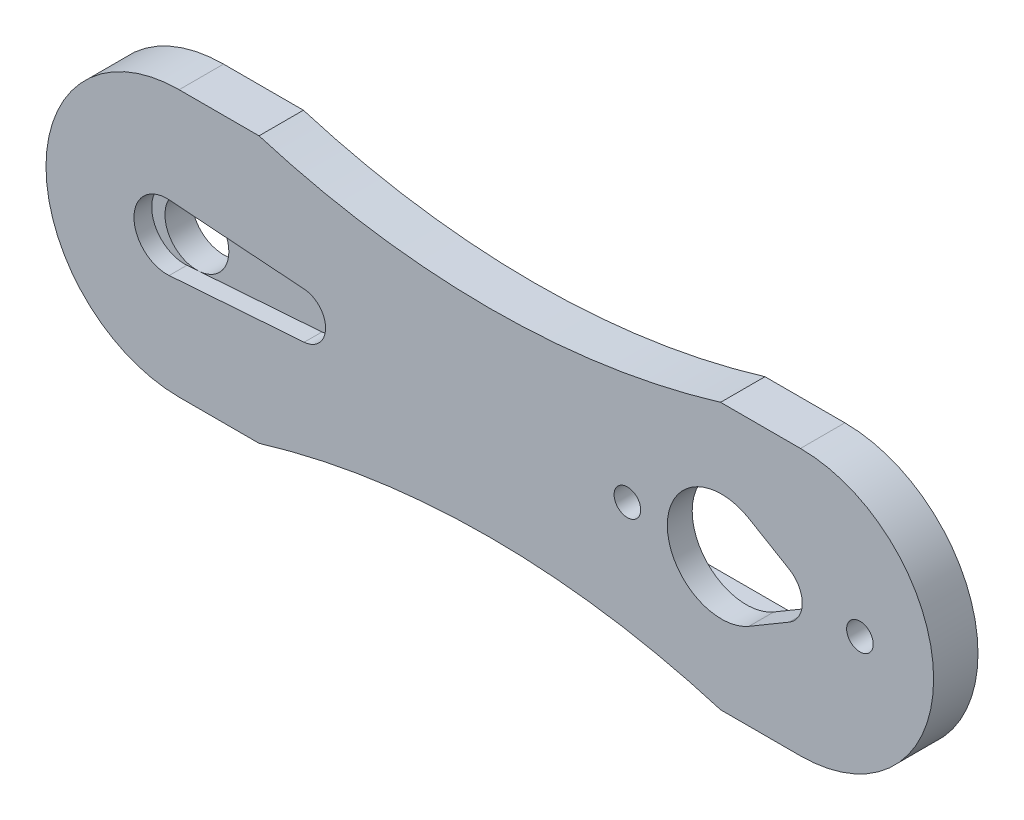
SolidWorks part; units mm, degrees
ref_plane "Front Plane" through (0, 0, 0) normal (0, 0, 1) x (1, 0, 0)
ref_plane "Top Plane" through (0, 0, 0) normal (0, 1, 0) x (1, 0, 0)
ref_plane "Right Plane" through (0, 0, 0) normal (1, 0, 0) x (0, 0, -1)
ref_plane "Plane1" through (0, 0, 0) normal (0, 0, -1) x (-1, 0, 0)
sketch "Sketch1" plane through (0, 0, 0) normal (0, 0, -1) x (-1, 0, 0)
  line L0 (-70, 0) -> (-61, 0)
  line L1 (0, 0) -> (-9, 0)
  line L2 (0, -15) -> (-10.6343, -15) construction
  line L3 (0, -30) -> (-9, -30)
  line L4 (-70, -30) -> (-61, -30)
  arc A1 (-61, 0) -> (-9, 0) centre (-35, 86.1626) ccw
  arc A2 (-61, -30) -> (-9, -30) centre (-35, -116.1626) cw
  circle A9 centre (0, -15) radius 3.6
  arc A11 (-70, 0) -> (-70, -30) centre (-70, -15) ccw
  arc A15 (0, -30) -> (0, 0) centre (0, -15) ccw
  dimension "D1" = 7.2
  dimension "D2" = 9
  dimension "D3" = 90
  dimension "D10" = 15
  dimension "D11" = 100
extrude "Boss-Extrude1" add sketch "Sketch1" against normal blind 5
sketch "Croquis1" plane through (0, 0, 5) normal (0, 0, 1) x (1, 0, 0)
  line L0 (-1.1238, -11.3096) -> (14.0871, -12.4067)
  line L1 (14.0871, -17.5933) -> (-1.1238, -18.6904)
  circle A0 centre (0, -15) radius 3.6 construction
  arc A1 (14.0871, -12.4067) -> (14.0871, -17.5933) centre (13.9, -15) cw
  circle A2 centre (0, -15) radius 3.6
  arc A4 (-1.1238, -11.3096) -> (-1.1238, -18.6904) centre (-1.39, -15) ccw
  point P8 (0, 0)
  point P9 (-1.1238, -11.3096)
  circle M4 centre (0, -15) radius 3.6
  dimension "D1" = 2.6
  dimension "D2" = 16.5
  dimension "D3" = 3.7
extrude "Cortar-Extruir1" cut sketch "Croquis1" against normal blind 2 contours A1 L0 L1 M4 | L0 A4 L1 M4
sketch "Croquis3" plane through (0, 0, 0) normal (0, 0, -1) x (-1, 0, 0)
  line L1 (-80, -8.5) -> (-47, -8.5)
  line L2 (-80, -8.5) -> (-80, -21.5)
  line L3 (-80, -21.5) -> (-47, -21.5)
  line L4 (-47, -8.5) -> (-47, -21.5)
  arc A0 (0, -30) -> (0, 0) centre (0, -15) ccw construction
  arc A5 (-70, 0) -> (-70, -30) centre (-70, -15) ccw construction
  point P7 (15, -15)
  point P8 (-47, -15)
  dimension "D1" = 33
  dimension "D2" = 13
  dimension "D3" = 5
extrude "Cortar-Extruir2" cut sketch "Croquis3" against normal blind 2.2
sketch "Croquis4" plane through (0, 0, 2.2) normal (0, 0, -1) x (-1, 0, 0)
  line L0 (-64.2, -9.7464) -> (-68.7246, -12.4163)
  line L1 (-64.2, -20.2536) -> (-68.7246, -17.5837)
  line L2 (-47, -21.5) -> (-47, -8.5) construction
  line L5 (-80, -8.5) -> (-80, -21.5) construction
  arc A1 (-64.2, -20.2536) -> (-64.2, -9.7464) centre (-61.1, -15) ccw
  arc A3 (-68.7246, -12.4163) -> (-68.7246, -17.5837) centre (-67.2, -15) ccw
  point P12 (-47, -15)
  dimension "D1" = 3
  dimension "D2" = 12.2
  dimension "D3" = 25
  dimension "D4" = 15.2
extrude "Cortar-Extruir3" cut sketch "Croquis4" against normal blind 3
sketch "Croquis6" plane through (0, 0, 2.2) normal (0, 0, -1) x (-1, 0, 0)
  circle A0 centre (-50.5, -15) radius 1.5
  arc A2 (-64.2, -20.2536) -> (-64.2, -9.7464) centre (-61.1, -15) ccw construction
  circle A3 centre (-76.7, -15) radius 1.5
  arc A4 (-68.7246, -12.4163) -> (-68.7246, -17.5837) centre (-67.2, -15) ccw construction
  point P11 (-55, -15)
  point P12 (-70.2, -15)
  dimension "D1" = 3
  dimension "D2" = 5
  dimension "D3" = 3
  dimension "D4" = 3
extrude "Cortar-Extruir4" cut sketch "Croquis6" against normal blind 3
